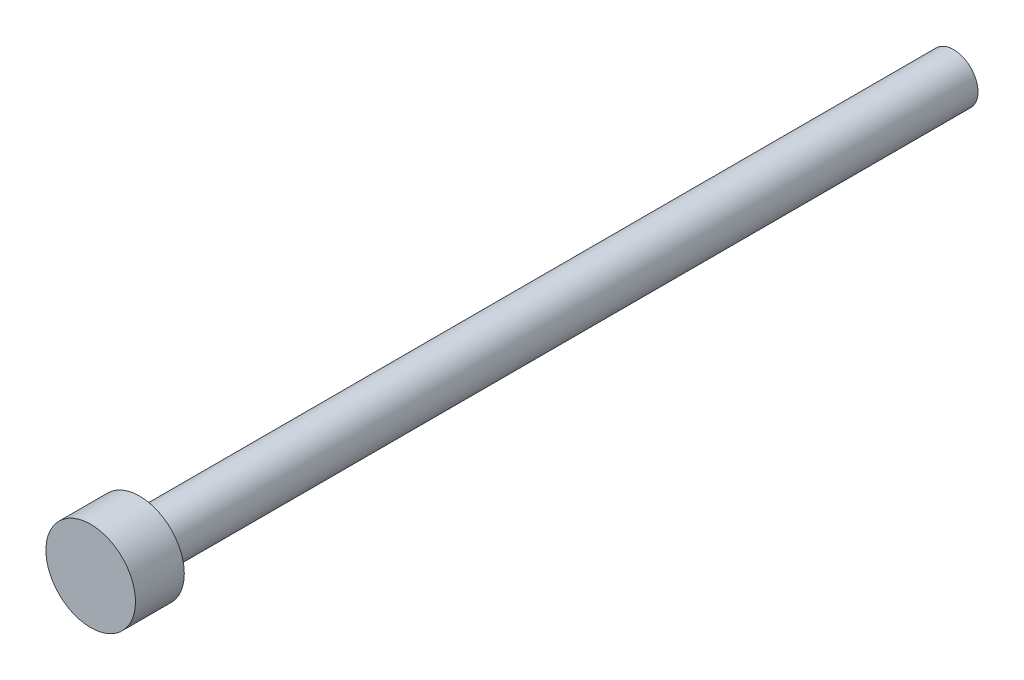
SolidWorks part; units mm, degrees
ref_plane "Front Plane" through (0, 0, 0) normal (0, 0, 1) x (1, 0, 0)
ref_plane "Top Plane" through (0, 0, 0) normal (0, 1, 0) x (1, 0, 0)
ref_plane "Right Plane" through (0, 0, 0) normal (1, 0, 0) x (0, 0, -1)
sketch "Shank_nominal_thread_envelope_profile" plane through (0, 0, 0) normal (0, 0, 1) x (1, 0, 0)
  circle A0 centre (0, 0) radius 1.5
  dimension "D1" = 3
extrude "Shank_nominal_thread_envelope" add sketch "Shank_nominal_thread_envelope_profile" along normal blind 50 from offset 50
sketch "Socket_head_envelope_profile" plane through (0, 0, 0) normal (0, 0, 1) x (1, 0, 0)
  circle A0 centre (0, 0) radius 2.75
  dimension "D1" = 5.5
extrude "Socket_head_envelope" add sketch "Socket_head_envelope_profile" along normal blind 3
